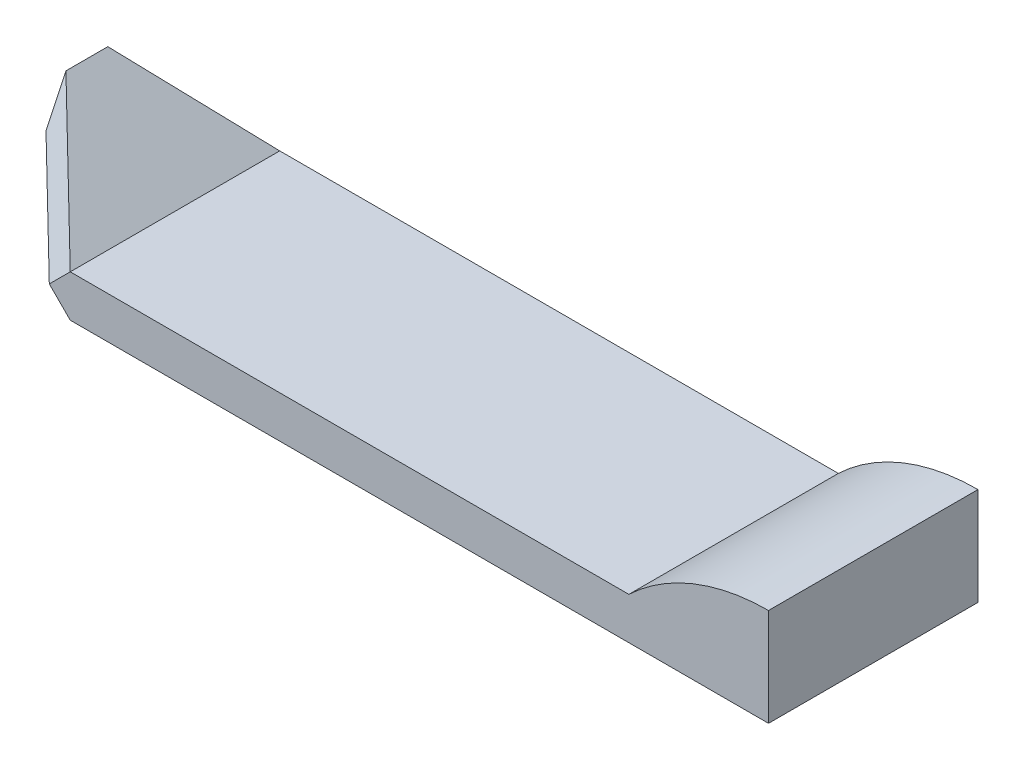
SolidWorks part; units mm, degrees
ref_plane "Front Plane" through (0, 0, 0) normal (0, 0, 1) x (1, 0, 0)
ref_plane "Top Plane" through (0, 0, 0) normal (0, 1, 0) x (1, 0, 0)
ref_plane "Right Plane" through (0, 0, 0) normal (1, 0, 0) x (0, 0, -1)
sketch "Sketch1" plane through (0, 0, 0) normal (0, 1, 0) x (1, 0, 0)
  line L1 (-125, 37.5) -> (125, 37.5)
  line L2 (-125, 37.5) -> (-125, -37.5)
  line L3 (-125, -37.5) -> (125, -37.5)
  line L4 (125, 37.5) -> (125, -37.5)
  line L5 (-125, 37.5) -> (125, -37.5) construction
  line L6 (-125, -37.5) -> (125, 37.5) construction
  point P0 (0, 0)
  dimension "D1" = 250
  dimension "D2" = 75
extrude "Boss-Extrude1" add sketch "Sketch1" along normal blind 15
sketch "Sketch3" plane through (0, 0, 0) normal (0, 0, 1) x (1, 0, 0)
  line L0 (125, 15) -> (125, 35)
  line L1 (-125, 15) -> (125, 15) construction
  line L2 (75, 15) -> (125, 15)
  arc A0 (125, 35) -> (75, 15) centre (125, -37.5) ccw
  dimension "D1" = 20
  dimension "D2" = 50
extrude "Boss-Extrude2" add sketch "Sketch3" along normal blind 37.5
mirror "Mirror1" about plane through (125, -37.5, 0) normal (0, 0, 1) of "Boss-Extrude2"
sketch "Sketch6" plane through (0, 0, 37.5) normal (0, 0, 1) x (1, 0, 0)
  line L5 (-125, 0) -> (-125, 15)
  line L6 (-125, 0) -> (-156.5456, 31.5456)
  line L7 (-125, 15) -> (-156.5456, 46.5456)
  line L8 (-156.5456, 31.5456) -> (-156.5456, 46.5456)
  line L9 (-125, 0) -> (125, 0) construction
  line L10 (-125, 15) -> (-125, 0) construction
  line L11 (-125, 15) -> (75, 15) construction
  dimension "D1" = 135
extrude "Boss-Extrude3" add sketch "Sketch6" against normal blind 75
sketch "Sketch7" plane through (-55, -55, 0) normal (0.7071, 0.7071, 0) x (0, 0, -1)
  line L0 (-37.5, 98.9949) -> (-7.5, 143.6072)
  line L1 (37.5, 143.6072) -> (-37.5, 143.6072) construction
  line L2 (-7.5, 143.6072) -> (-37.5, 143.6072)
  line L3 (7.5, 143.6072) -> (37.5, 98.9949)
  line L4 (37.5, 98.9949) -> (37.5, 143.6072)
  line L7 (-37.5, 143.6072) -> (-37.5, 98.9949)
  line L8 (37.5, 143.6072) -> (7.5, 143.6072)
  dimension "D1" = 30
  dimension "D2" = 30
extrude "Cut-Extrude1" cut sketch "Sketch7" against normal blind 75
